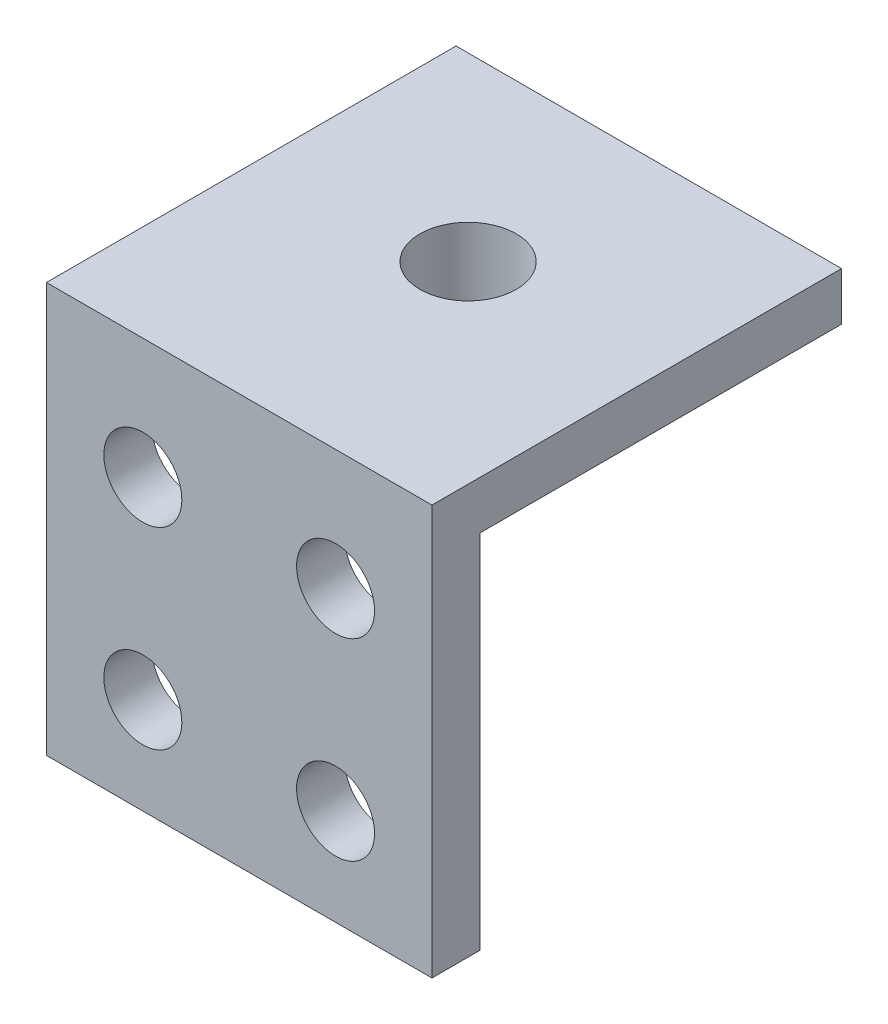
SolidWorks part; units mm, degrees
ref_plane "Plan de face" through (0, 0, 0) normal (0, 0, 1) x (1, 0, 0)
ref_plane "Plan de dessus" through (0, 0, 0) normal (0, 1, 0) x (1, 0, 0)
ref_plane "Plan de droite" through (0, 0, 0) normal (1, 0, 0) x (0, 0, -1)
sketch "Esquisse1" plane through (0, 0, 0) normal (1, 0, 0) x (0, 0, -1)
  line L0 (0, 0) -> (25.4, 0)
  line L1 (0, 0) -> (0, -25.4)
  dimension "D1" = 25.4
  dimension "D2" = 25.4
ref_plane "Plan1" through (0, -25.4, 0) normal (0, 1, 0) x (-1, 0, 0)
sketch "Esquisse2" plane through (0, -25.4, 0) normal (0, 1, 0) x (-1, 0, 0)
  line L1 (12.7, 1.5875) -> (-12.7, 1.5875)
  line L2 (12.7, 1.5875) -> (12.7, -1.5875)
  line L3 (12.7, -1.5875) -> (-12.7, -1.5875)
  line L4 (-12.7, 1.5875) -> (-12.7, -1.5875)
  line L5 (12.7, 1.5875) -> (-12.7, -1.5875) construction
  line L6 (12.7, -1.5875) -> (-12.7, 1.5875) construction
  point P0 (0, 0)
  dimension "D1" = 25.4
  dimension "D2" = 3.175
sweep "Balayage1" add profiles "Esquisse2" path "Esquisse1"
sketch "Esquisse3" plane through (0, -1.5875, 0) normal (0, -1, 0) x (1, 0, 0)
  line L0 (12.7, -1.5875) -> (12.7, -25.4) construction
  line L1 (-12.7, -1.5875) -> (-12.7, -25.4) construction
  line L2 (12.7, -13.4938) -> (-12.7, -13.4937) construction
  line L4 (2.6303, -19.8438) -> (6.35, -16.124)
  line L5 (6.35, -16.124) -> (6.35, -10.8635)
  line L6 (6.35, -10.8635) -> (2.6303, -7.1437)
  line L7 (2.6303, -7.1437) -> (-2.6303, -7.1437)
  line L8 (-2.6303, -7.1437) -> (-6.35, -10.8635)
  line L9 (-6.35, -10.8635) -> (-6.35, -16.124)
  line L10 (-6.35, -16.124) -> (-2.6303, -19.8438)
  line L11 (-2.6303, -19.8438) -> (2.6303, -19.8438)
  circle A0 centre (0, -13.4937) radius 6.35 construction
  point P0 (12.7, -13.4938)
  point P1 (-12.7, -13.4937)
  point P8 (0, -13.4937)
  dimension "D1" = 12.7
extrude "Boss.-Extru.1" add sketch "Esquisse3" along normal blind 6.35
sketch "Esquisse5" plane through (0, -7.9375, 0) normal (0, -1, 0) x (1, 0, 0)
  line L0 (6.35, -16.124) -> (6.35, -10.8635) construction
  line L1 (-6.35, -10.8635) -> (-6.35, -16.124) construction
  line L2 (-2.6303, -19.8438) -> (2.6303, -19.8438) construction
  line L3 (2.6303, -7.1437) -> (-2.6303, -7.1437) construction
  line L4 (6.35, -13.4937) -> (-6.35, -13.4937) construction
  line L5 (0, -19.8438) -> (0, -7.1437) construction
  circle A0 centre (0, -13.4937) radius 3.175
  point P0 (6.35, -13.4937)
  point P1 (-6.35, -13.4938)
  point P4 (0, -19.8438)
  point P7 (0, -7.1437)
extrude "Enlèv. mat.-Extru.1" cut sketch "Esquisse5" against normal through all
sketch "Esquisse7" plane through (0, 0, -1.5875) normal (0, 0, -1) x (-1, 0, 0)
  line L0 (-12.7, -1.5875) -> (-12.7, -25.4) construction
  line L1 (-12.7, -25.4) -> (12.7, -25.4) construction
  circle A0 centre (-6.35, -19.05) radius 2.5695
  circle A1 centre (-6.35, -6.35) radius 2.5695
  circle A2 centre (6.35, -19.05) radius 2.5695
  circle A3 centre (6.35, -6.35) radius 2.5695
  dimension "D1" = 6.35
  dimension "D2" = 6.35
  dimension "D3" = 2
  dimension "D4" = 2
extrude "Enlèv. mat.-Extru.2" cut sketch "Esquisse7" against normal through all
